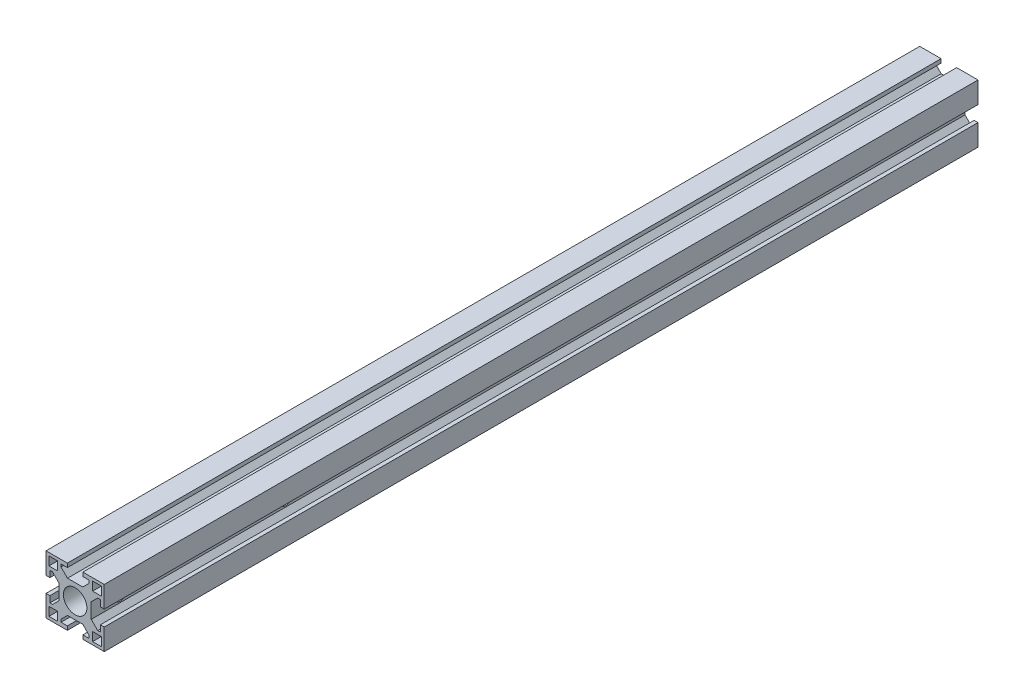
SolidWorks part; units mm, degrees
ref_plane "Ebene vorne" through (0, 0, 0) normal (0, 0, 1) x (1, 0, 0)
ref_plane "Ebene oben" through (0, 0, 0) normal (0, 1, 0) x (1, 0, 0)
ref_plane "Ebene rechts" through (0, 0, 0) normal (1, 0, 0) x (0, 0, -1)
ref_plane "Ebene1" through (0, 0, 0) normal (0, 0, -1) x (-1, 0, 0)
sketch "Skizze1" plane through (0, 0, 0) normal (0, 0, -1) x (-1, 0, 0)
  line L0 (15, -15) -> (15, -4)
  line L1 (15, -4) -> (13, -4)
  line L2 (13, -4) -> (13, -7.2657)
  line L3 (13, -7.2657) -> (11.6343, -7.2657)
  line L4 (11.6343, -7.2657) -> (8.3, -3.9314)
  line L5 (8.3, -3.9314) -> (8.3, 3.9314)
  line L6 (8.3, 3.9314) -> (11.6343, 7.2657)
  line L7 (11.6343, 7.2657) -> (13, 7.2657)
  line L8 (13, 7.2657) -> (13, 4)
  line L9 (13, 4) -> (15, 4)
  line L10 (15, 4) -> (15, 15)
  line L11 (15, 15) -> (4, 15)
  line L12 (4, 15) -> (4, 13)
  line L13 (4, 13) -> (7.2657, 13)
  line L14 (7.2657, 13) -> (7.2657, 11.6343)
  line L15 (7.2657, 11.6343) -> (3.9314, 8.3)
  line L16 (3.9314, 8.3) -> (-3.9314, 8.3)
  line L17 (-3.9314, 8.3) -> (-7.2657, 11.6343)
  line L18 (-7.2657, 11.6343) -> (-7.2657, 13)
  line L19 (-7.2657, 13) -> (-4, 13)
  line L20 (-4, 13) -> (-4, 15)
  line L21 (-4, 15) -> (-15, 15)
  line L22 (-15, 15) -> (-15, 4)
  line L23 (-15, 4) -> (-13, 4)
  line L24 (-13, 4) -> (-13, 7.2657)
  line L25 (-13, 7.2657) -> (-11.6343, 7.2657)
  line L26 (-11.6343, 7.2657) -> (-8.3, 3.9314)
  line L27 (-8.3, 3.9314) -> (-8.3, -3.9314)
  line L28 (-8.3, -3.9314) -> (-11.6343, -7.2657)
  line L29 (-11.6343, -7.2657) -> (-13, -7.2657)
  line L30 (-13, -7.2657) -> (-13, -4)
  line L31 (-13, -4) -> (-15, -4)
  line L32 (-15, -4) -> (-15, -15)
  line L33 (-15, -15) -> (-4, -15)
  line L34 (-4, -15) -> (-4, -13)
  line L35 (-4, -13) -> (-7.2657, -13)
  line L36 (-7.2657, -13) -> (-7.2657, -11.6343)
  line L37 (-7.2657, -11.6343) -> (-3.9314, -8.3)
  line L38 (-3.9314, -8.3) -> (3.9314, -8.3)
  line L39 (3.9314, -8.3) -> (7.2657, -11.6343)
  line L40 (7.2657, -11.6343) -> (7.2657, -13)
  line L41 (7.2657, -13) -> (4, -13)
  line L42 (4, -13) -> (4, -15)
  line L43 (4, -15) -> (15, -15)
  line L44 (9, 13.5) -> (13.5, 13.5)
  line L45 (13.5, 13.5) -> (13.5, 9)
  line L46 (13.5, 9) -> (9, 9)
  line L47 (9, 9) -> (9, 13.5)
  line L48 (13.5, -9) -> (13.5, -13.5)
  line L49 (13.5, -13.5) -> (9, -13.5)
  line L50 (9, -13.5) -> (9, -9)
  line L51 (9, -9) -> (13.5, -9)
  line L52 (-9, -13.5) -> (-13.5, -13.5)
  line L53 (-13.5, -13.5) -> (-13.5, -9)
  line L54 (-13.5, -9) -> (-9, -9)
  line L55 (-9, -9) -> (-9, -13.5)
  line L56 (-13.5, 9) -> (-13.5, 13.5)
  line L57 (-13.5, 13.5) -> (-9, 13.5)
  line L58 (-9, 13.5) -> (-9, 9)
  line L59 (-9, 9) -> (-13.5, 9)
  circle A0 centre (0, 0) radius 6.05
extrude "Aufsatz-Linear austragen1" add sketch "Skizze1" against normal blind 450
sketch "Skizze3" plane through (-15, 0, 0) normal (-1, 0, 0) x (0, 0, 1)
  line L0 (450, -15) -> (450, -4) construction
  circle A0 centre (435, 0) radius 3.3
  circle A1 centre (350, 0) radius 3.3
  dimension "D1" = 85
  dimension "D2" = 15
  dimension "D3" = 6.6
extrude "Schnitt-Linear austragen2" cut sketch "Skizze3" against normal through all
